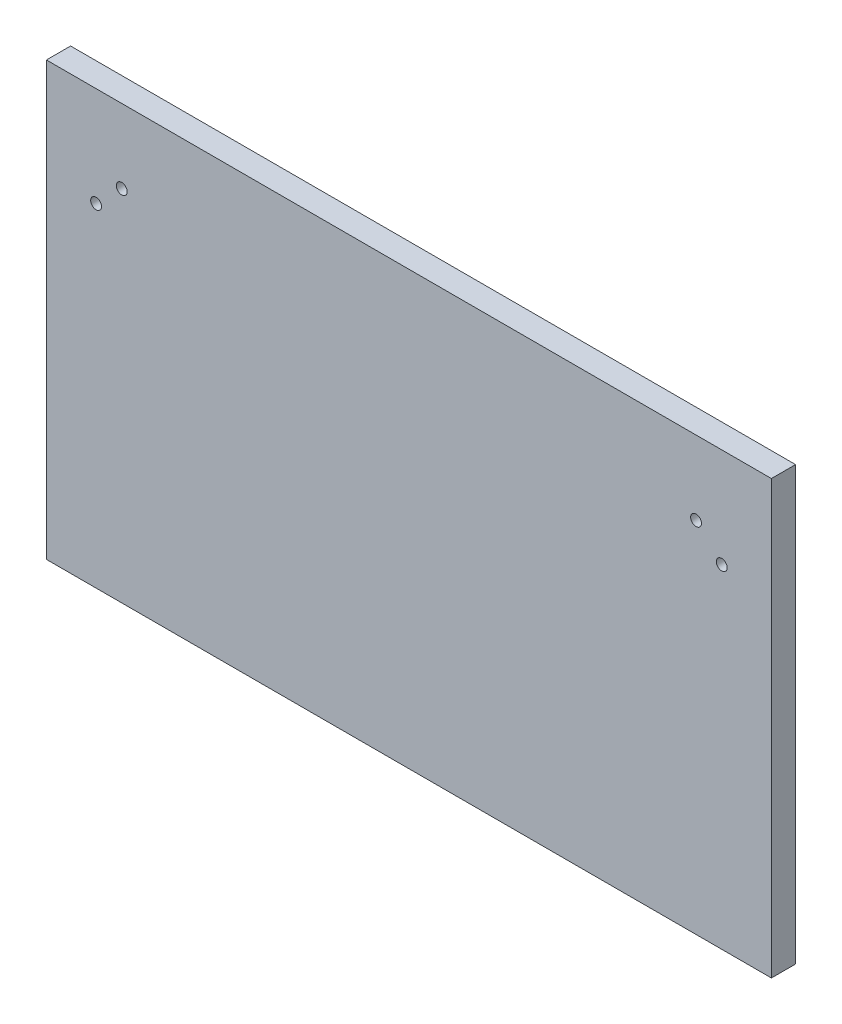
SolidWorks part; units mm, degrees
material "Multistrato di pioppo"
ref_plane "Piano frontale" through (0, 0, 0) normal (0, 0, 1) x (1, 0, 0)
ref_plane "Piano superiore" through (0, 0, 0) normal (0, 1, 0) x (1, 0, 0)
ref_plane "Piano destro" through (0, 0, 0) normal (1, 0, 0) x (0, 0, -1)
sketch "Schizzo1" plane through (0, 0, 0) normal (0, 0, 1) x (1, 0, 0)
  line L1 (0, 0) -> (-300, 0)
  line L2 (0, 0) -> (0, 179)
  line L3 (0, 179) -> (-300, 179)
  line L4 (-300, 0) -> (-300, 179)
  dimension "D1" = 300
  dimension "D2" = 179
extrude "Estrusione-Estrusione1" add sketch "Schizzo1" along normal blind 10
sketch "Schizzo3" plane through (0, 0, 10) normal (0, 0, 1) x (1, 0, 0)
  circle A0 centre (-31.1612, 148.4454) radius 2.25
  circle A1 centre (-20.5546, 137.8388) radius 2.25
  circle A2 centre (-268.8388, 148.4454) radius 2.25
  circle A3 centre (-279.4454, 137.8388) radius 2.25
  dimension "D1" = 4.5
extrude "Taglio-Estrusione2" cut sketch "Schizzo3" against normal blind 10
